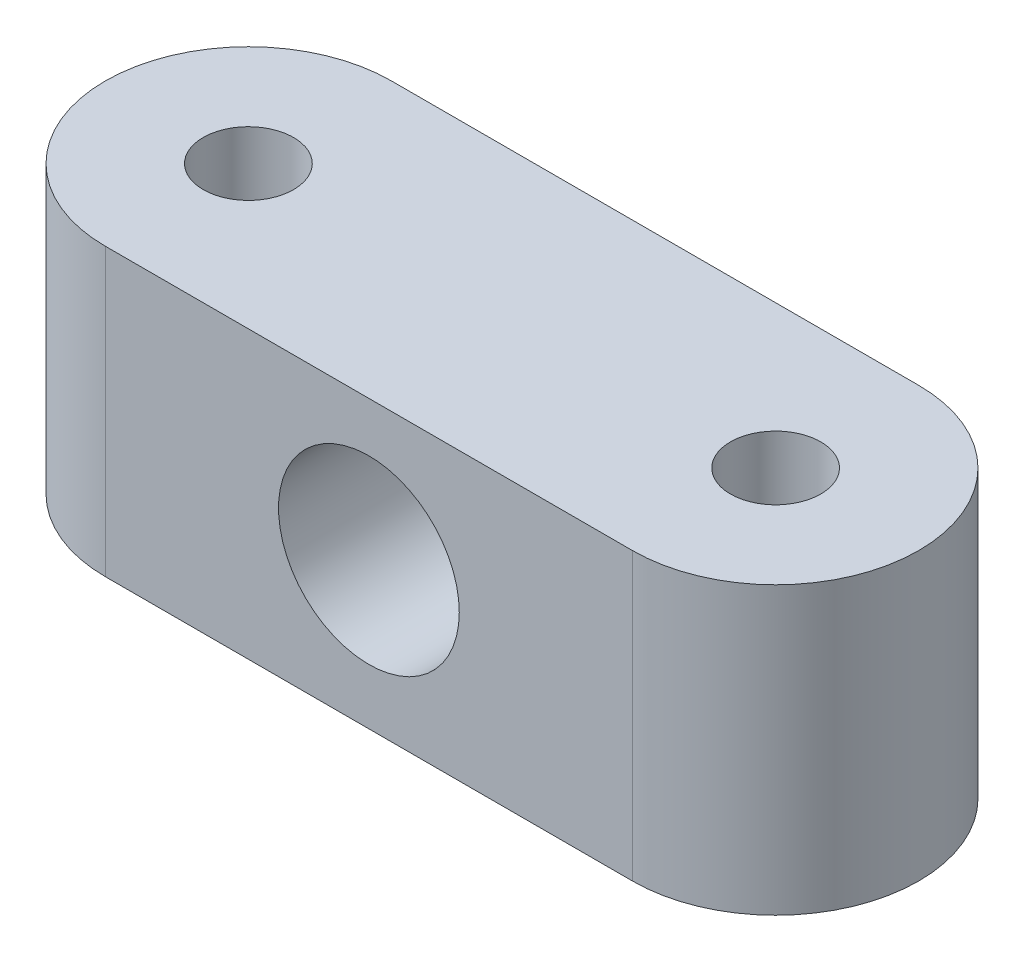
SolidWorks part; units mm, degrees
ref_plane "Płaszczyzna przednia" through (0, 0, 0) normal (0, 0, 1) x (1, 0, 0)
ref_plane "Płaszczyzna górna" through (0, 0, 0) normal (0, 1, 0) x (1, 0, 0)
ref_plane "Płaszczyzna prawa" through (0, 0, 0) normal (1, 0, 0) x (0, 0, -1)
sketch "Szkic1" plane through (0, 0, 0) normal (0, 1, 0) x (1, 0, 0)
  line L0 (0, 0) -> (70, 0) construction
  line L1 (0, 19) -> (70, 19)
  line L2 (0, -19) -> (70, -19)
  arc A0 (0, 19) -> (0, -19) centre (0, 0) ccw
  arc A1 (70, -19) -> (70, 19) centre (70, 0) ccw
  circle A2 centre (0, 0) radius 6
  circle A3 centre (70, 0) radius 6
  point P3 (35, 0)
  dimension "D2" = 19
  dimension "D3" = 12
  dimension "D1" = 70
extrude "Dodanie-wyciągnięcie1" add sketch "Szkic1" along normal blind 38
sketch "Szkic2" plane through (0, 0, 19) normal (0, 0, 1) x (1, 0, 0)
  line L0 (35, 0) -> (35, 51.7271) construction
  line L1 (0, 0) -> (70, 0) construction
  circle A0 centre (35, 19.4026) radius 12
  dimension "D1" = 24
extrude "Wytnij-wyciągnięcie2" cut sketch "Szkic2" against normal through all
cosmetic thread "Oznaczenie gwintu3" parameters "D1"=5, "D2"=27
